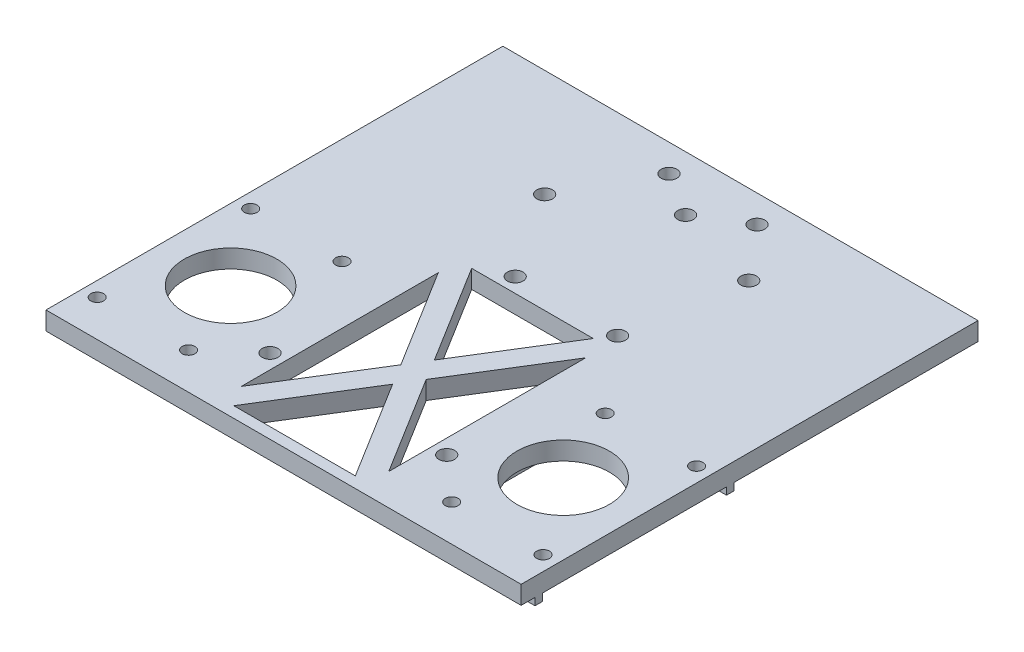
SolidWorks part; units mm, degrees
ref_plane "Front Plane" through (0, 0, 0) normal (0, 0, 1) x (1, 0, 0)
ref_plane "Top Plane" through (0, 0, 0) normal (0, 1, 0) x (1, 0, 0)
ref_plane "Right Plane" through (0, 0, 0) normal (1, 0, 0) x (0, 0, -1)
sketch "Sketch1" plane through (0, 0, 0) normal (0, 1, 0) x (1, 0, 0)
  line L1 (-65, 62.5) -> (65, 62.5)
  line L2 (-65, 62.5) -> (-65, -62.5)
  line L3 (-65, -62.5) -> (65, -62.5)
  line L4 (65, 62.5) -> (65, -62.5)
  line L5 (-65, 62.5) -> (65, -62.5) construction
  line L6 (-65, -62.5) -> (65, 62.5) construction
  point P0 (0, 0)
  dimension "D1" = 130
  dimension "D2" = 125
extrude "Boss-Extrude1" add sketch "Sketch1" along normal blind 5
sketch "Sketch2" plane through (0, 5, 0) normal (0, 1, 0) x (1, 0, 0)
  line L1 (-65, -62.5) -> (65, -62.5) construction
  line L2 (-65, 62.5) -> (-65, -62.5) construction
  circle A0 centre (-61, -52.5) radius 1.75
  circle A1 centre (-36, -52.5) radius 1.75
  circle A2 centre (-36, -10.5) radius 1.75
  circle A3 centre (-61, -10.5) radius 1.75
  circle A4 centre (-45.5, -31.5) radius 12.65
  dimension "D2" = 25.3
  dimension "D7" = 3.5
  dimension "D8" = 3.5
  dimension "D9" = 3.5
  dimension "D10" = 3.5
  dimension "D1" = 19.5
  dimension "D3" = 31
  dimension "D4" = 4
  dimension "D5" = 10
  dimension "D6" = 10
  dimension "D11" = 4
  dimension "D12" = 42
  dimension "D13" = 42
  dimension "D14" = 25
  dimension "D15" = 25
extrude "Cut-Extrude1" cut sketch "Sketch2" against normal blind 10
ref_plane "Plane1" through (0, 0, 0) normal (-1, 0, 0) x (0, 0, 1)
ref_plane "Plane2" through (0, 0, 0) normal (0, 0, 1) x (1, 0, 0)
mirror "Mirror3" about plane through (0, 0, 0) normal (-1, 0, 0) of "Cut-Extrude1"
sketch "Sketch3" plane through (0, 5, 0) normal (0, 1, 0) x (1, 0, 0)
  line L0 (-65, -62.5) -> (65, -62.5) construction
  line L1 (-65, 62.5) -> (-65, -62.5) construction
  line L2 (65, -62.5) -> (65, 62.5) construction
  line L3 (65, 62.5) -> (-65, 62.5) construction
  circle A0 centre (-24.17, -42.03) radius 2.15
  circle A1 centre (24.17, -42.03) radius 2.15
  circle A2 centre (-8.73, 9.6) radius 2.15
  circle A3 centre (19.29, 9.6) radius 2.15
  circle A4 centre (-24.17, 33.11) radius 2.15
  circle A5 centre (24.17, 40.6) radius 2.15
  dimension "D1" = 4.3
  dimension "D6" = 4.3
  dimension "D7" = 4.3
  dimension "D10" = 4.3
  dimension "D11" = 4.3
  dimension "D12" = 4.3
  dimension "D2" = 20.47
  dimension "D3" = 40.83
  dimension "D4" = 20.47
  dimension "D5" = 40.83
  dimension "D8" = 72.1
  dimension "D9" = 56.27
  dimension "D13" = 45.71
  dimension "D14" = 72.1
  dimension "D15" = 29.39
  dimension "D16" = 21.9
  dimension "D17" = 40.83
extrude "Cut-Extrude2" cut sketch "Sketch3" against normal blind 10
sketch "Sketch4" plane through (0, 5, 0) normal (0, 1, 0) x (1, 0, 0)
  line L0 (0, 62.5) -> (0, 47.5) construction
  line L1 (65, 62.5) -> (-65, 62.5) construction
  line L2 (-12.0498, 55) -> (12.0498, 55) construction
  circle A0 centre (0, 47.5) radius 2.15
  circle A1 centre (12.0498, 55) radius 2.15
  circle A2 centre (-12.0498, 55) radius 2.15
  point P9 (0, 55)
  dimension "D2" = 4.3
  dimension "D3" = 4.3
  dimension "D4" = 4.3
  dimension "D1" = 15
  dimension "D5" = 24.0996
extrude "Cut-Extrude3" cut sketch "Sketch4" against normal blind 10
sketch "Sketch5" plane through (0, 0, 0) normal (0, -1, 0) x (1, 0, 0)
  line L0 (-58.15, 31.5) -> (-65, 31.5) construction
  line L1 (-65, -62.5) -> (-65, 62.5) construction
  line L2 (-65, 56.7) -> (-65, 6.3)
  line L3 (-65, 56.7) -> (-31.6, 56.7)
  line L4 (-31.6, 56.7) -> (-31.6, 6.3)
  line L5 (-31.6, 6.3) -> (-65, 6.3)
  line L6 (-65, 58.7) -> (-29.6, 58.7)
  line L7 (-29.6, 58.7) -> (-29.6, 4.3)
  line L8 (-29.6, 4.3) -> (-65, 4.3)
  line L9 (-65, 4.3) -> (-65, 6.3)
  line L10 (-65, 58.7) -> (-65, 56.7)
  circle A0 centre (-45.5, 31.5) radius 12.65 construction
  point P10 (-65, 31.5)
  line M39 (-65, 62.5) -> (-65, -62.5)
  dimension "D1" = 50.4
  dimension "D2" = 33.4
  dimension "D3" = 2
  dimension "D4" = 2
  dimension "D5" = 2
extrude "Boss-Extrude2" add sketch "Sketch5" along normal blind 2 contours L8 L7 L6 L3 L4 L5 M39
mirror "Mirror5" about plane through (0, 0, 0) normal (-1, 0, 0) of "Boss-Extrude2"
sketch "Sketch6" plane through (0, 0, 0) normal (0, -1, 0) x (1, 0, 0)
  circle A0 centre (-12.0498, -55) radius 2.65
  circle A1 centre (12.0498, -55) radius 2.65
  circle A2 centre (0, -47.5) radius 2.65
  circle A3 centre (24.17, -40.6) radius 2.65
  circle A4 centre (-24.17, -33.11) radius 2.65
  circle A5 centre (-8.73, -9.6) radius 2.65
  circle A6 centre (19.29, -9.6) radius 2.65
  circle A7 centre (-61, 10.5) radius 2.65
  circle A8 centre (-61, 52.5) radius 2.65
  circle A9 centre (-36, 52.5) radius 2.65
  circle A10 centre (-36, 10.5) radius 2.65
  circle A11 centre (-24.17, 42.03) radius 2.65
  circle A12 centre (24.17, 42.03) radius 2.65
  circle A13 centre (36, 52.5) radius 2.65
  circle A14 centre (36, 10.5) radius 2.65
  circle A15 centre (61, 10.5) radius 2.65
  circle A16 centre (61, 52.5) radius 2.65
  dimension "D1" = 5.3
  dimension "D2" = 5.3
  dimension "D3" = 5.3
  dimension "D4" = 5.3
  dimension "D5" = 5.3
  dimension "D6" = 5.3
  dimension "D7" = 5.3
  dimension "D8" = 5.3
  dimension "D9" = 5.3
  dimension "D10" = 5.3
  dimension "D11" = 5.3
  dimension "D12" = 5.3
  dimension "D13" = 5.3
  dimension "D14" = 5.3
  dimension "D15" = 5.3
  dimension "D16" = 5.3
  dimension "D17" = 5.3
extrude "Cut-Extrude4" cut sketch "Sketch6" against normal blind 0.5
sketch "Sketch7" plane through (0, 0, 0) normal (0, -1, 0) x (1, 0, 0)
  line L0 (-65, 62.5) -> (65, 62.5) construction
  line L1 (-20.17, 59.5) -> (20.17, 59.5)
  line L2 (-20.17, 59.5) -> (-20.17, -5.6)
  line L3 (-20.17, -5.6) -> (20.17, -5.6)
  line L4 (20.17, 59.5) -> (20.17, -5.6)
  line L5 (-20.17, 59.5) -> (20.17, -5.6) construction
  line L6 (-20.17, -5.6) -> (20.17, 59.5) construction
  line L7 (-16.6299, 59.5) -> (0, 32.6629)
  line L8 (0, 32.6629) -> (16.6299, 59.5)
  line L9 (20.17, 53.9) -> (3.4701, 26.95)
  line L10 (3.4701, 26.95) -> (20.17, 0)
  line L11 (16.6299, -5.6) -> (0, 21.2371)
  line L12 (0, 21.2371) -> (-16.6299, -5.6)
  line L13 (-20.17, 0) -> (-3.4701, 26.95)
  line L14 (-3.4701, 26.95) -> (-20.17, 53.9)
  circle A0 centre (-24.17, 42.03) radius 2.65 construction
  circle A1 centre (24.17, 42.03) radius 2.65 construction
  circle A2 centre (-8.73, -9.6) radius 2.65 construction
  point P23 (0, 0)
  point P25 (0, 26.95)
  point P26 (0, 0)
  dimension "D1" = 3
  dimension "D2" = 4
  dimension "D3" = 4
  dimension "D4" = 4
extrude "Cut-Extrude5" cut sketch "Sketch7" against normal through all contours L13 L14 L2 | L7 L8 L1 | L9 L10 L4 | L11 L12 L3
sketch "Sketch8" plane through (0, 0, 0) normal (0, -1, 0) x (1, 0, 0)
  line L0 (65, -62.5) -> (-65, -62.5) construction
  line L1 (-60.3724, -8.6) -> (-34.173, -8.6)
  line L2 (-60.3724, -8.6) -> (-60.3724, -59.5)
  line L3 (-60.3724, -59.5) -> (-34.173, -59.5)
  line L4 (-34.173, -8.6) -> (-34.173, -59.5)
  line L5 (34.3154, -8.6) -> (60.5147, -8.6)
  line L6 (34.3154, -8.6) -> (34.3154, -59.5)
  line L7 (34.3154, -59.5) -> (60.5147, -59.5)
  line L8 (60.5147, -8.6) -> (60.5147, -59.5)
  line L9 (-16.6299, -5.6) -> (16.6299, -5.6) construction
  line L10 (-60.3724, -8.6) -> (-34.173, -59.5) construction
  line L11 (-60.3724, -59.5) -> (-34.173, -8.6) construction
  line L12 (34.3154, -8.6) -> (60.5147, -59.5) construction
  line L13 (34.3154, -59.5) -> (60.5147, -8.6) construction
  line L14 (-58.5991, -8.6) -> (-47.2727, -30.6049)
  line L15 (-47.2727, -30.6049) -> (-35.9463, -8.6)
  line L16 (-34.173, -12.9209) -> (-45.0486, -34.05)
  line L17 (-45.0486, -34.05) -> (-34.173, -55.1791)
  line L18 (-35.7916, -59.5) -> (-47.2727, -37.1945)
  line L19 (-47.2727, -37.1945) -> (-58.7538, -59.5)
  line L20 (-60.3724, -55.7485) -> (-49.2037, -34.05)
  line L21 (-49.2037, -34.05) -> (-60.3724, -12.3515)
  line L22 (37.2468, -8.6) -> (47.4151, -28.9379)
  line L23 (47.4151, -28.9379) -> (57.6963, -8.6)
  line L24 (60.5147, -12.7437) -> (50.2515, -34.05)
  line L25 (50.2515, -34.05) -> (60.5147, -55.3176)
  line L26 (57.6963, -59.5) -> (47.4151, -39.4342)
  line L27 (47.4151, -39.4342) -> (37.2468, -59.5)
  line L28 (34.3154, -55.3176) -> (43.8434, -34.05)
  line L29 (43.8434, -34.05) -> (34.3154, -13.6503)
  point P36 (0, 0)
  point P37 (-45.0486, -34.05)
  point P41 (-47.2727, -34.05)
  point P44 (47.4151, -34.05)
  dimension "D1" = 3
  dimension "D2" = 3
  dimension "D3" = 3
  dimension "D4" = 3
